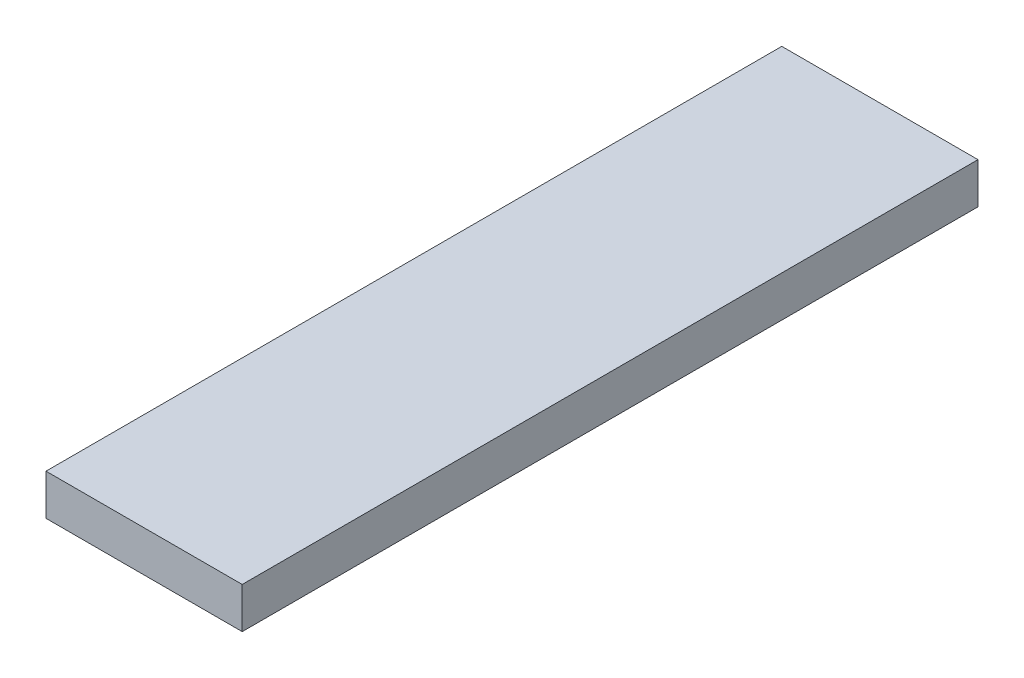
SolidWorks part; units mm, degrees
material "Ti-3Al-8V-6Cr-4Mo-4Zr (SS)"
ref_plane "Front Plane" through (0, 0, 0) normal (0, 0, 1) x (1, 0, 0)
ref_plane "Top Plane" through (0, 0, 0) normal (0, 1, 0) x (1, 0, 0)
ref_plane "Right Plane" through (0, 0, 0) normal (1, 0, 0) x (0, 0, -1)
sketch "Sketch1" plane through (0, 0, 0) normal (0, 1, 0) x (1, 0, 0)
  line L1 (-7.62, 0) -> (7.62, 0)
  line L2 (-7.62, 0) -> (-7.62, 57.15)
  line L3 (-7.62, 57.15) -> (7.62, 57.15)
  line L4 (7.62, 0) -> (7.62, 57.15)
  dimension "D1" = 15.24
  dimension "D2" = 57.15
extrude "Boss-Extrude1" add sketch "Sketch1" along normal blind 3.175
